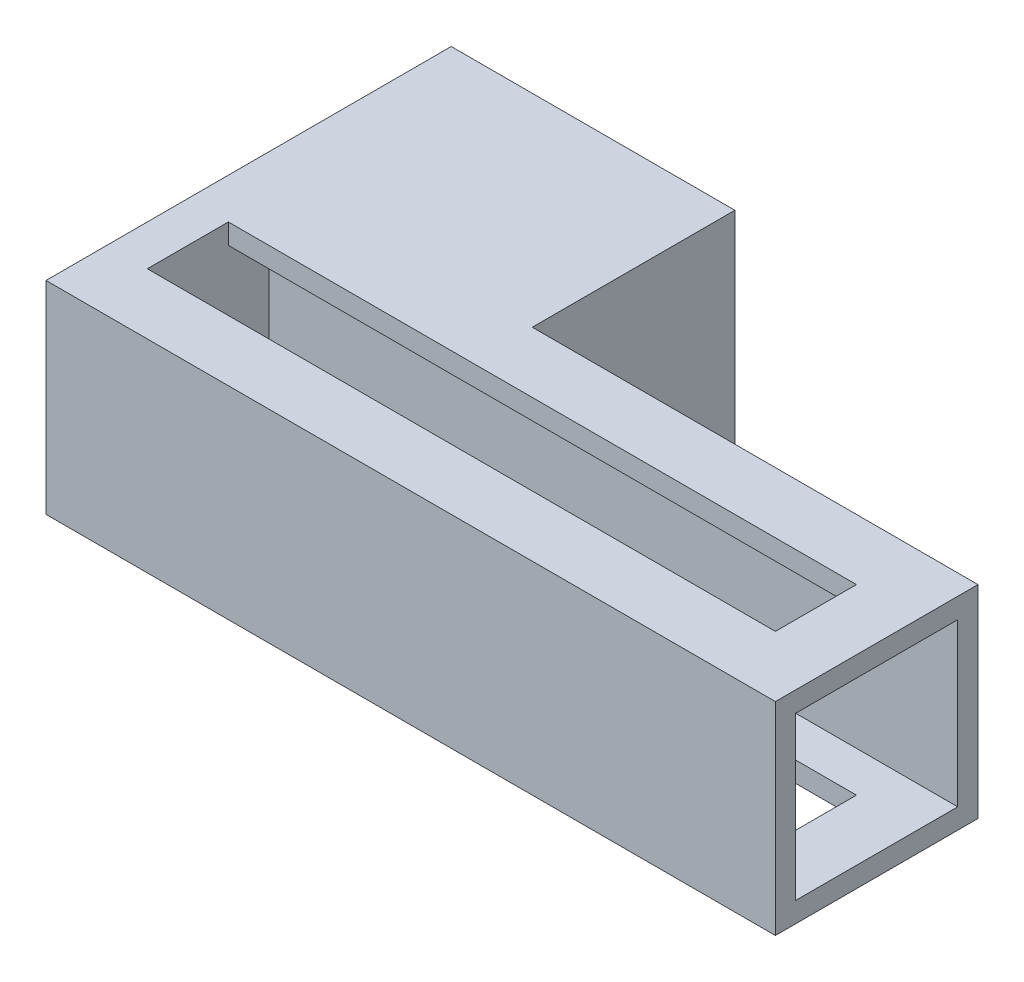
SolidWorks part; units mm, degrees
ref_plane "Alzado" through (0, 0, 0) normal (0, 0, 1) x (1, 0, 0)
ref_plane "Planta" through (0, 0, 0) normal (0, 1, 0) x (1, 0, 0)
ref_plane "Vista lateral" through (0, 0, 0) normal (1, 0, 0) x (0, 0, -1)
sketch "Croquis1" plane through (0, 0, 0) normal (0, 0, 1) x (1, 0, 0)
  line L1 (-35, -25) -> (35, -25)
  line L2 (-35, -25) -> (-35, 25)
  line L3 (-35, 25) -> (35, 25)
  line L4 (35, -25) -> (35, 25)
  line L5 (-35, -25) -> (35, 25) construction
  line L6 (-35, 25) -> (35, -25) construction
  point P0 (0, 0)
  dimension "D1" = 50
  dimension "D2" = 70
extrude "Saliente-Extruir1" add sketch "Croquis1" along normal blind 50
sketch "Croquis2" plane through (-35, 0, 0) normal (-1, 0, 0) x (0, 0, 1)
  line L0 (50, -25) -> (50, 25)
  line L1 (50, 25) -> (100, 25)
  line L2 (100, 25) -> (100, -25)
  line L3 (100, -25) -> (50, -25)
  dimension "D1" = 50
extrude "Saliente-Extruir2" add sketch "Croquis2" against normal blind 180
sketch "Croquis3" plane through (145, 0, 0) normal (1, 0, 0) x (0, 0, -1)
  line L0 (-50, 0) -> (-100, 0) construction
  line L1 (-50, 25) -> (-50, -25) construction
  line L2 (-100, -25) -> (-100, 25) construction
  line L3 (-75, 0) -> (-75, 20) construction
  line L4 (-55, 20) -> (-95, 20)
  line L5 (-95, 20) -> (-95, -20)
  line L6 (-55, 20) -> (-55, -20)
  line L7 (-55, -20) -> (-95, -20)
  point P13 (-55, 0)
  point P14 (-95, 0)
  dimension "D1" = 20
  dimension "D2" = 20
  dimension "D3" = 20
extrude "Cortar-Extruir1" cut sketch "Croquis3" against normal blind 170
sketch "Croquis4" plane through (0, -25, 0) normal (0, -1, 0) x (1, 0, 0)
  line L0 (145, 75) -> (-25, 75) construction
  line L1 (145, 50) -> (145, 100) construction
  line L2 (-25, 95) -> (-25, 55) construction
  line L3 (60, 75) -> (60, 85) construction
  line L4 (60, 85) -> (-25, 85)
  line L5 (-25, 85) -> (-25, 65)
  line L6 (60, 85) -> (130, 85)
  line L7 (130, 85) -> (130, 65)
  line L8 (60, 65) -> (130, 65)
  line L9 (60, 65) -> (-25, 65)
  point P12 (130, 75)
  dimension "D1" = 10
  dimension "D2" = 70
extrude "Cortar-Extruir2" cut sketch "Croquis4" against normal blind 50
